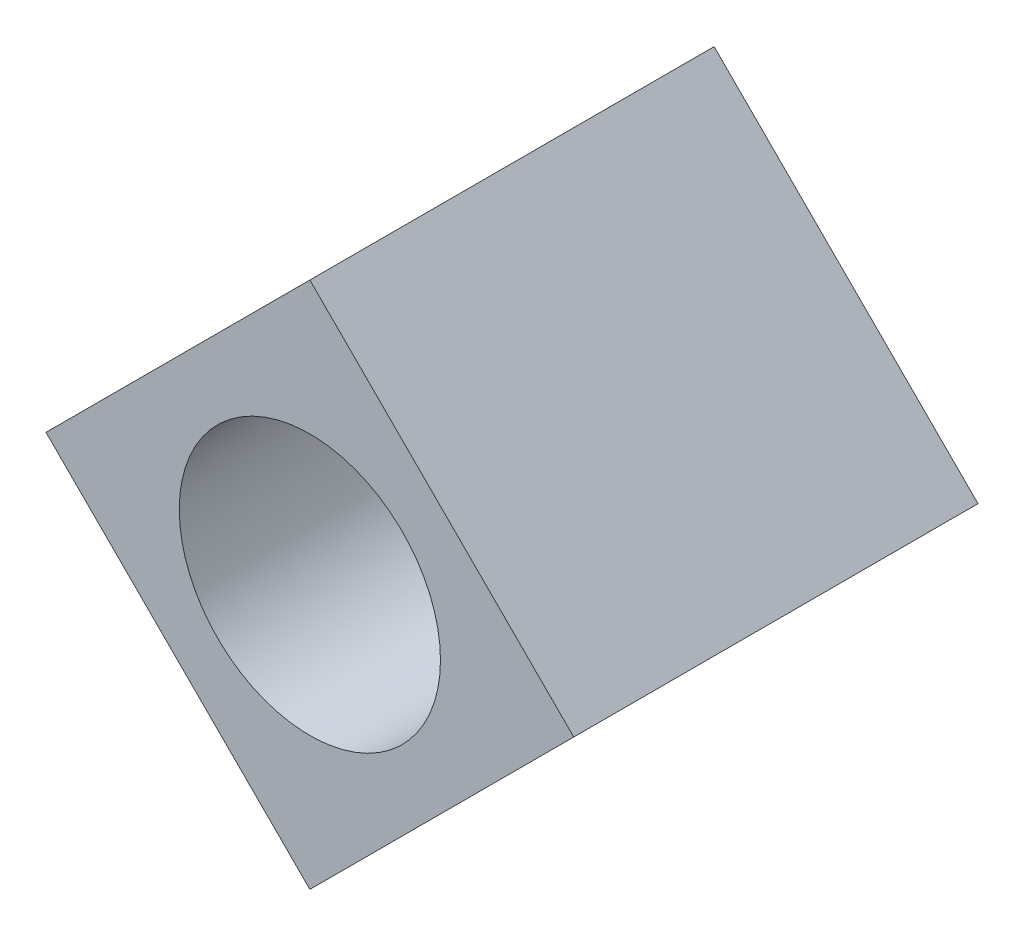
SolidWorks part; units mm, degrees
ref_plane "正面" through (0, 0, 0) normal (0, 0, 1) x (1, 0, 0)
ref_plane "平面" through (0, 0, 0) normal (0, 1, 0) x (1, 0, 0)
ref_plane "右側面" through (0, 0, 0) normal (1, 0, 0) x (0, 0, -1)
sketch "ｽｹｯﾁ1" plane through (0, 0, 0) normal (0, 0, 1) x (1, 0, 0)
  line L1 (4.2426, 0) -> (0, 4.2426)
  line L2 (0, 4.2426) -> (-4.2426, 0)
  line L3 (-4.2426, 0) -> (0, -4.2426)
  line L4 (0, -4.2426) -> (4.2426, 0)
  circle A0 centre (0, 0) radius 2.1
  circle A1 centre (0, 0) radius 3 construction
  dimension "D1" = 4.2
  dimension "D2" = 6
extrude "ﾎﾞｽ - 押し出し1" add sketch "ｽｹｯﾁ1" along normal blind 6.5
